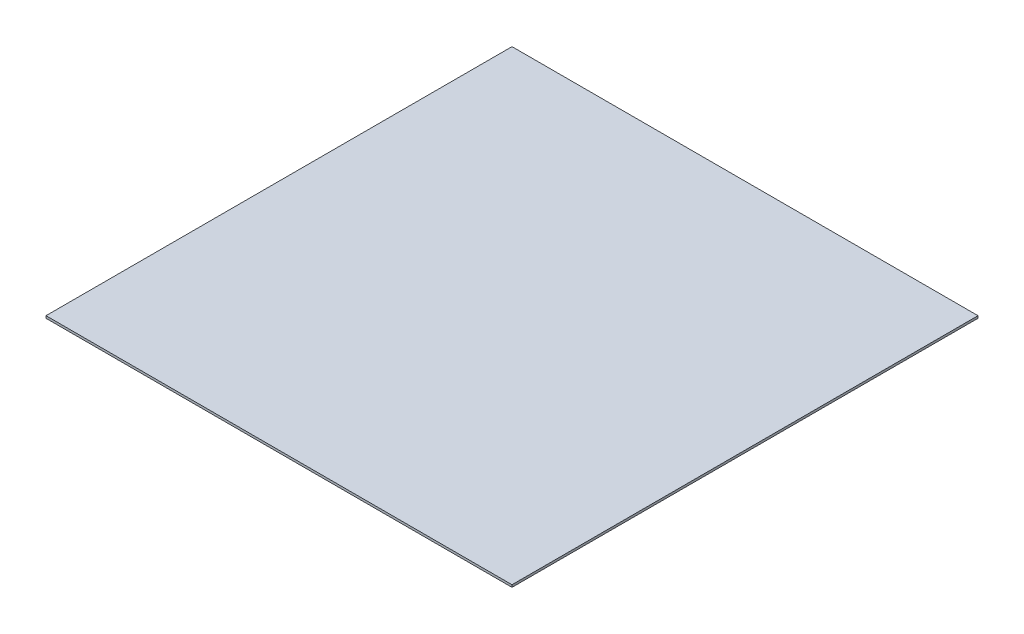
SolidWorks part; units mm, degrees
ref_plane "Front Plane" through (0, 0, 0) normal (0, 0, 1) x (1, 0, 0)
ref_plane "Top Plane" through (0, 0, 0) normal (0, 1, 0) x (1, 0, 0)
ref_plane "Right Plane" through (0, 0, 0) normal (1, 0, 0) x (0, 0, -1)
sketch "Sketch1" plane through (0, 0, 0) normal (0, 1, 0) x (1, 0, 0)
  line L1 (152, -152) -> (-152, -152)
  line L2 (152, -152) -> (152, 152)
  line L3 (152, 152) -> (-152, 152)
  line L4 (-152, -152) -> (-152, 152)
  line L5 (152, -152) -> (-152, 152) construction
  line L6 (152, 152) -> (-152, -152) construction
  point P0 (0, 0)
  dimension "D1" = 304
extrude "Boss-Extrude1" add sketch "Sketch1" along normal blind 1.5
